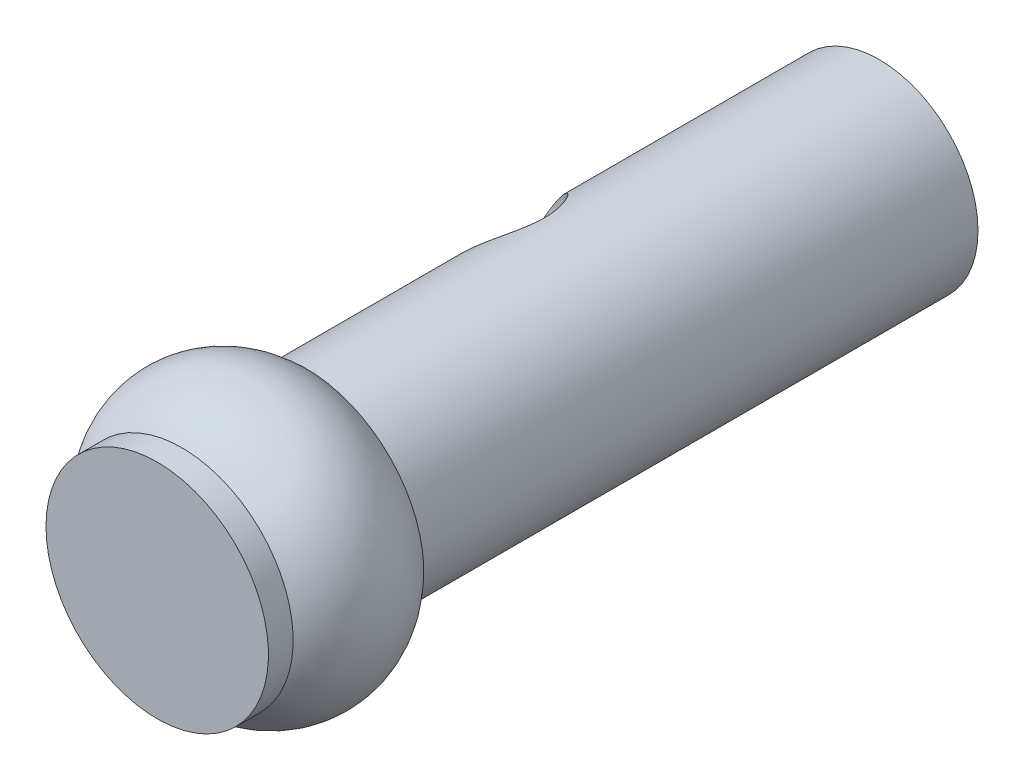
SolidWorks part; units mm, degrees
ref_plane "Plan de face" through (0, 0, 0) normal (0, 0, 1) x (1, 0, 0)
ref_plane "Plan de dessus" through (0, 0, 0) normal (0, 1, 0) x (1, 0, 0)
ref_plane "Plan de droite" through (0, 0, 0) normal (1, 0, 0) x (0, 0, -1)
sketch "Esquisse2" plane through (0, 0, 0) normal (0, 1, 0) x (1, 0, 0)
  line L0 (0, 12.7802) -> (0, -17.4698) construction
  line L1 (7, 43.3427) -> (7, -3.0046)
  line L2 (7, -3.0046) -> (0, -3.0046)
  line L3 (0, -3.0046) -> (0, -12.6573)
  line L4 (9, -13.0786) -> (9, -15.0786)
  line L5 (9, -15.0786) -> (0, -15.0786)
  line L6 (9.5, -3.0046) -> (8, -3.0046)
  line L7 (8, -3.0046) -> (8, 43.3427)
  line L8 (8, 43.3427) -> (7, 43.3427)
  line L9 (0, -15.0786) -> (0, -12.6573)
  arc A0 (9.5, -3.0046) -> (9, -13.0786) centre (4.4015, -7.801) cw
  dimension "D6" = 7
  dimension "D1" = 1
  dimension "D2" = 1.5
  dimension "D3" = 14
  dimension "D4" = 18
  dimension "D5" = 2
revolve "Révolution1" add sketch "Esquisse2" angle 360 about L0
hole_wizard "Trou de passage d'axe 3/321" positions "Esquisse3D1" profile "Esquisse3" hole size "3/32" standard "PCS"
sketch3d "Esquisse3D1"
  point P0 (-6.6815, 4.3997, -19.3427)
  dimension "D1" = 24
sketch "Esquisse3" plane through (-6.6815, 4.3997, -19.3427) normal (0, 0, 1) x (-0.55, -0.8352, 0)
  line L0 (0, 0) -> (0, 1)
  line L1 (0, 1) -> (4.5, 1)
  line L2 (4.5, 1) -> (4.5, 0)
  line L5 (4.5, 0) -> (0, 0)
  line L11 (0, -6.35) -> (0, 107.95) construction
  dimension "Diamètre du perçage jusqu'au prochain" = 9
  dimension "Profondeur du perçage jusqu'au prochain" = 1
